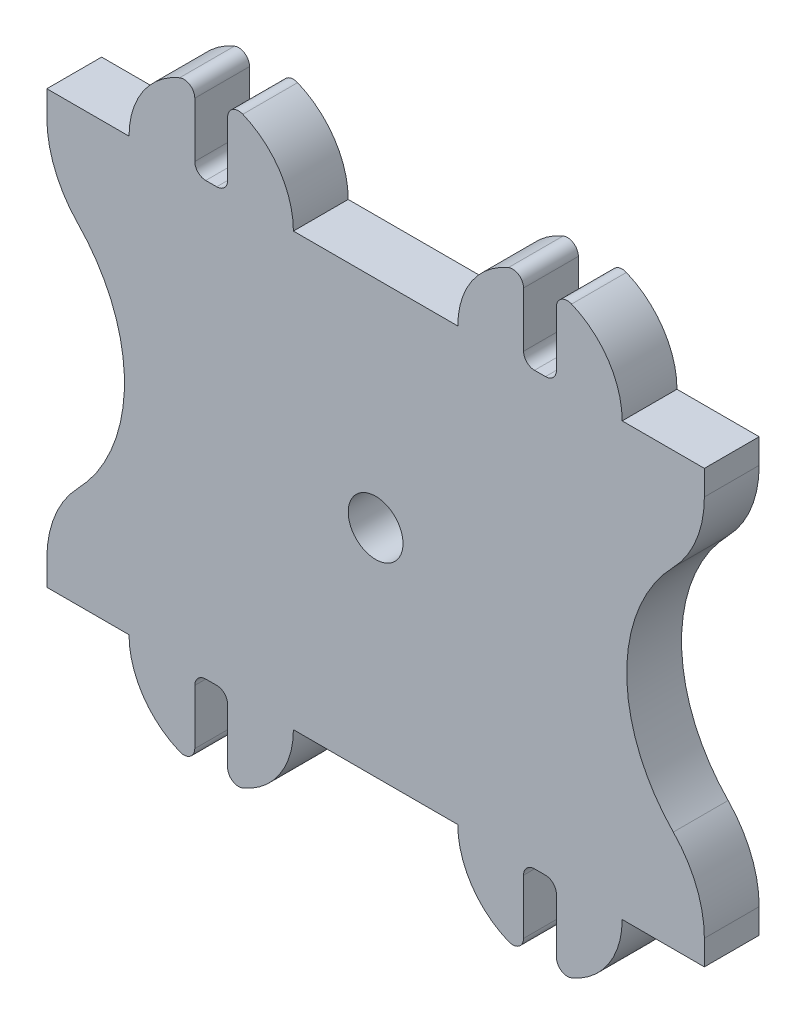
SolidWorks part; units mm, degrees
ref_plane "Plan de face" through (0, 0, 0) normal (0, 0, 1) x (1, 0, 0)
ref_plane "Plan de dessus" through (0, 0, 0) normal (0, 1, 0) x (1, 0, 0)
ref_plane "Plan de droite" through (0, 0, 0) normal (1, 0, 0) x (0, 0, -1)
sketch "Esquisse1" plane through (0, 0, 0) normal (0, 0, 1) x (1, 0, 0)
  line L0 (0, 27.5394) -> (0, -27.5394) construction
  line L1 (-30, 19.7) -> (-22.5, 19.7)
  line L2 (-30, 19.7) -> (-30, -19.7)
  line L3 (-30, -19.7) -> (-22.5, -19.7)
  line L4 (30, 19.7) -> (30, -19.7)
  line L5 (-30, 19.7) -> (30, -19.7) construction
  line L6 (-30, -19.7) -> (30, 19.7) construction
  line L10 (-15, 22.9326) -> (-15, 16.4674) construction
  line L11 (-16.5, 25.7) -> (-16.5, 20.7)
  line L12 (-13.5, 25.7) -> (-13.5, 20.7)
  line L13 (-15.5, 19.7) -> (-14.5, 19.7)
  line L14 (-7.5, 19.7) -> (7.5, 19.7)
  line L15 (13.5, 25.7) -> (13.5, 20.7)
  line L16 (15.5, 19.7) -> (14.5, 19.7)
  line L17 (16.5, 25.7) -> (16.5, 20.7)
  line L18 (14.5, 19.7) -> (15.5, 19.7)
  line L19 (22.5, 19.7) -> (30, 19.7)
  line L20 (-23.0943, 0) -> (23.0943, 0) construction
  line L21 (-13.5, -25.7) -> (-13.5, -20.7)
  line L22 (-15.5, -19.7) -> (-14.5, -19.7)
  line L23 (-16.5, -25.7) -> (-16.5, -20.7)
  line L24 (16.5, -25.7) -> (16.5, -20.7)
  line L25 (15.5, -19.7) -> (14.5, -19.7)
  line L26 (13.5, -25.7) -> (13.5, -20.7)
  line L27 (-15.5, -19.7) -> (-14.5, -19.7)
  line L28 (-7.5, -19.7) -> (7.5, -19.7)
  line L29 (14.5, -19.7) -> (15.5, -19.7)
  line L30 (22.5, -19.7) -> (30, -19.7)
  circle A0 centre (0, 0) radius 2.5
  arc A2 (-7.5, 19.7) -> (-12.1154, 26.6231) centre (-15, 19.7) ccw
  arc A3 (-17.8846, 26.6231) -> (-22.5, 19.7) centre (-15, 19.7) ccw
  arc A4 (-13.5, 25.7) -> (-12.1154, 26.6231) centre (-12.5, 25.7) cw
  arc A5 (-16.5, 25.7) -> (-17.8846, 26.6231) centre (-17.5, 25.7) ccw
  arc A6 (-16.5, 20.7) -> (-15.5, 19.7) centre (-15.5, 20.7) ccw
  arc A7 (-13.5, 20.7) -> (-14.5, 19.7) centre (-14.5, 20.7) cw
  arc A8 (7.5, 19.7) -> (12.1154, 26.6231) centre (15, 19.7) cw
  arc A9 (13.5, 25.7) -> (12.1154, 26.6231) centre (12.5, 25.7) ccw
  arc A10 (13.5, 20.7) -> (14.5, 19.7) centre (14.5, 20.7) ccw
  arc A11 (16.5, 20.7) -> (15.5, 19.7) centre (15.5, 20.7) cw
  arc A12 (16.5, 25.7) -> (17.8846, 26.6231) centre (17.5, 25.7) cw
  arc A13 (17.8846, 26.6231) -> (22.5, 19.7) centre (15, 19.7) cw
  arc A14 (-7.5, -19.7) -> (-12.1154, -26.6231) centre (-15, -19.7) cw
  arc A15 (-13.5, -25.7) -> (-12.1154, -26.6231) centre (-12.5, -25.7) ccw
  arc A16 (-13.5, -20.7) -> (-14.5, -19.7) centre (-14.5, -20.7) ccw
  arc A17 (-16.5, -20.7) -> (-15.5, -19.7) centre (-15.5, -20.7) cw
  arc A18 (-16.5, -25.7) -> (-17.8846, -26.6231) centre (-17.5, -25.7) cw
  arc A19 (-17.8846, -26.6231) -> (-22.5, -19.7) centre (-15, -19.7) cw
  arc A20 (17.8846, -26.6231) -> (22.5, -19.7) centre (15, -19.7) ccw
  arc A21 (16.5, -25.7) -> (17.8846, -26.6231) centre (17.5, -25.7) ccw
  arc A22 (16.5, -20.7) -> (15.5, -19.7) centre (15.5, -20.7) ccw
  arc A23 (13.5, -20.7) -> (14.5, -19.7) centre (14.5, -20.7) cw
  arc A24 (13.5, -25.7) -> (12.1154, -26.6231) centre (12.5, -25.7) cw
  arc A25 (7.5, -19.7) -> (12.1154, -26.6231) centre (15, -19.7) ccw
  point P0 (0, 0)
  point P10 (0, 0)
  point P17 (-15, 19.7)
  point P23 (-13.5, 27.0485)
  point P26 (-16.5, 27.0485)
  point P29 (-16.5, 19.7)
  point P32 (-13.5, 19.7)
  point P51 (0, 0)
  dimension "D1" = 5
  dimension "D5" = 15
  dimension "D7" = 1
  dimension "D8" = 1
  dimension "D9" = 1
  dimension "D2" = 60
  dimension "D3" = 39.4
  dimension "D4" = 15
  dimension "D6" = 1.5
extrude "Boss.-Extru.1" add sketch "Esquisse1" along normal blind 5 contours L28 A25 A24 L26 A23 L25 A22 L24 A21 A20 L30 L4 L19 A13 A12 L17 A11 L16 A10 L15 A9 A8 L14 A2 A4 L12 A7 L13 A6 L11 A5 A3 L1 L2 L3 A19 A18 L23 A17 L22 A16 L21 A15 A14 A0
sketch "Esquisse2" plane through (0, 0, 5) normal (0, 0, 1) x (1, 0, 0)
  line L0 (-30, 19.7) -> (-30, -19.7) construction
  line L1 (0, 22.4605) -> (0, -22.4605) construction
  line L2 (-30, 12.7412) -> (-30, -12.7412)
  line L3 (30, 12.7412) -> (30, -12.7412)
  arc A0 (-30, 12.7412) -> (-30, -12.7412) centre (-37.9159, 0) cw
  arc A1 (30, 12.7412) -> (30, -12.7412) centre (37.9159, 0) ccw
  point P3 (-30, 0)
  point P10 (0, 0)
  dimension "D1" = 15
extrude "Enlèv. mat.-Extru.1" cut sketch "Esquisse2" against normal through all
fillet "Congé1" radius 10 4 edges at (30, -12.7412, 2.5) (30, 12.7412, 2.5) (-30, 12.7412, 2.5) (-30, -12.7412, 2.5)
